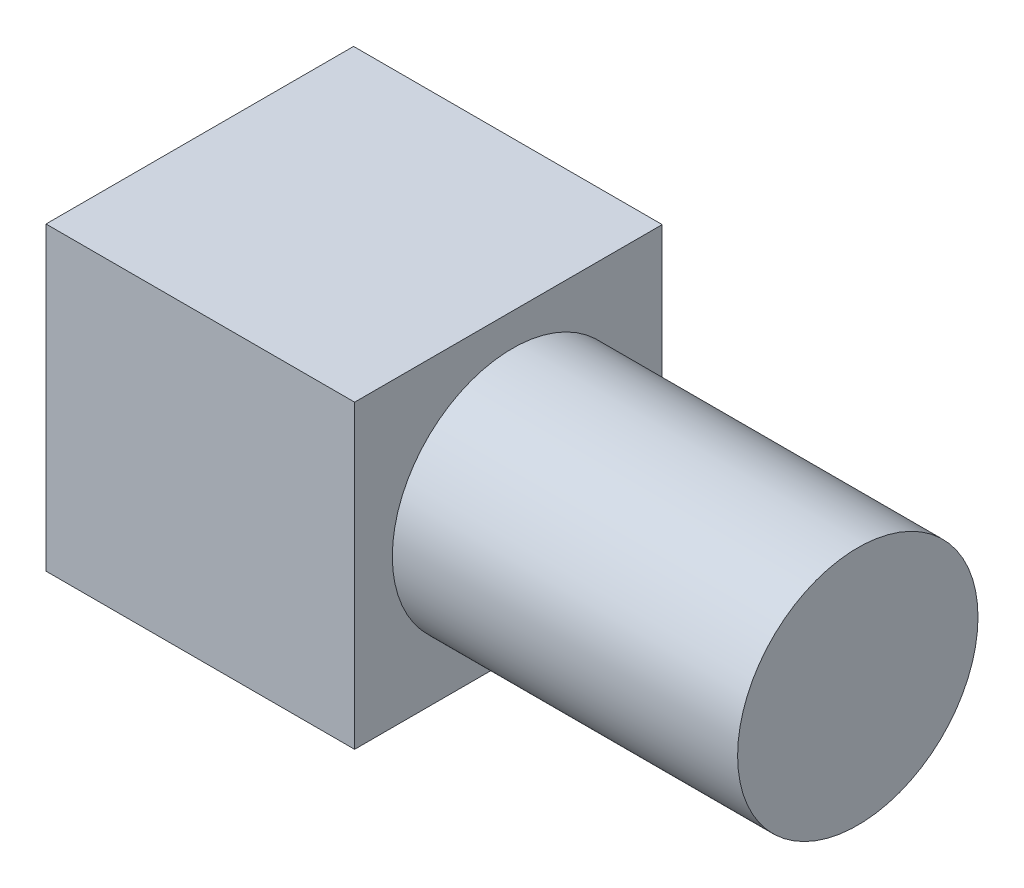
SolidWorks part; units mm, degrees
ref_plane "Front Plane" through (0, 0, 0) normal (0, 0, 1) x (1, 0, 0)
ref_plane "Top Plane" through (0, 0, 0) normal (0, 1, 0) x (1, 0, 0)
ref_plane "Right Plane" through (0, 0, 0) normal (1, 0, 0) x (0, 0, -1)
sketch "Sketch1" plane through (0, 0, 0) normal (0, 1, 0) x (1, 0, 0)
  line L1 (-55.7541, 23.9667) -> (19.1734, 23.9667)
  line L2 (-55.7541, 23.9667) -> (-55.7541, -50.7085)
  line L3 (-55.7541, -50.7085) -> (19.1734, -50.7085)
  line L4 (19.1734, 23.9667) -> (19.1734, -50.7085)
extrude "Boss-Extrude1" add sketch "Sketch1" along normal blind 73
sketch "Sketch2" plane through (0, 0, 0) normal (1, 0, 0) x (0, 0, -1)
  circle A0 centre (-12.3721, 35.9742) radius 29.1819
extrude "Boss-Extrude2" add sketch "Sketch2" along normal blind 103
scale "Scale1" scale about centroid uniform scaling yes scale factor 0.18
